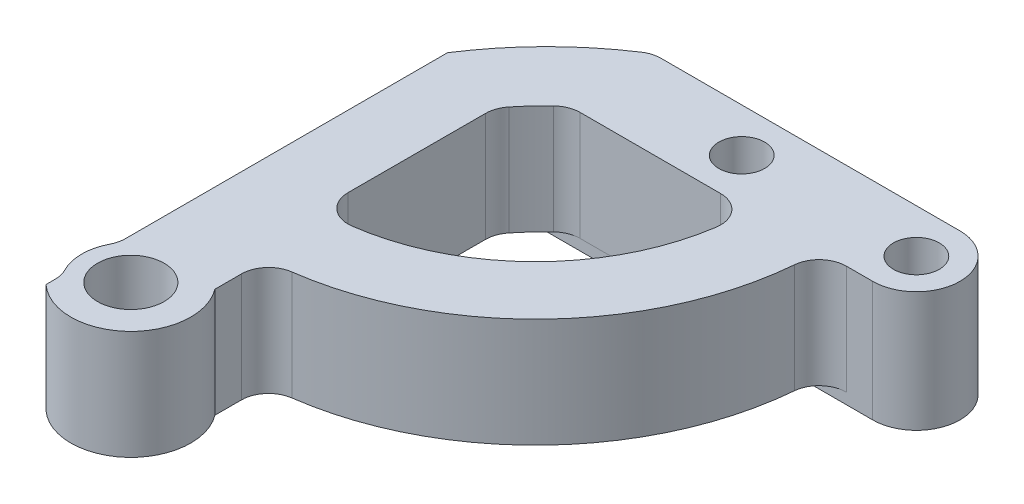
SolidWorks part; units mm, degrees
ref_plane "Front" through (0, 0, 0) normal (0, 0, 1) x (1, 0, 0)
ref_plane "Top" through (0, 0, 0) normal (0, 1, 0) x (1, 0, 0)
ref_plane "Right" through (0, 0, 0) normal (1, 0, 0) x (0, 0, -1)
sketch "Sketch1" plane through (0, 0, 0) normal (0, 1, 0) x (1, 0, 0)
  line L1 (-115.2537, -11) -> (-131.7843, -11)
  line L2 (-141.618, -49.1231) -> (-141.618, -47.6052)
  line L3 (-135.0594, -14.5432) -> (-135.0767, -30.6507)
  line L6 (-133.5072, -41.7607) -> (-133.5072, -37.0672)
  line L7 (-141.618, -42.5351) -> (-141.618, -12.3375)
  line L8 (-104, -3) -> (-132.1358, -3)
  line L9 (-104, -11) -> (-108.8005, -11)
  circle A26 centre (-104, -7) radius 2.1
  circle A27 centre (-120, -7) radius 2.1
  arc A32 (-104, -11) -> (-104, -3) centre (-104, -7) ccw
  arc A38 (-133.5072, -37.0672) -> (-108.8005, -11) centre (-134.9051, -11) ccw
  arc A40 (-132.1358, -3) -> (-141.618, -12.3375) centre (-115.9362, -28.9341) ccw
  arc A44 (-131.7843, -11) -> (-135.0594, -14.5432) centre (-115.9362, -28.9341) ccw
  arc A45 (-135.0767, -30.6507) -> (-115.2537, -11) centre (-134.9051, -11) ccw
  circle A50 centre (-137.9001, -45.0701) radius 3.05
  arc A52 (-141.618, -49.1231) -> (-133.5072, -41.7607) centre (-137.9001, -45.0701) ccw
  arc A53 (-141.618, -42.5351) -> (-141.618, -47.6052) centre (-137.9001, -45.0701) ccw
extrude "Boss-Extrude1" add sketch "Sketch1" along normal blind 11
fillet "Fillet1" radius 2.5 9 edges at (-132.1358, 5.5, 3) (-108.8005, 5.5, 11) (-135.0594, 5.5, 14.5432) (-135.0767, 5.5, 30.6507) (-115.2537, 5.5, 11) (-131.7843, 5.5, 11) (-133.5072, 5.5, 37.0672) (-141.618, 5.5, 42.5351) (-141.618, 5.5, 47.6052)
sketch "Sketch3" plane through (0, 0, 0) normal (0, -1, 0) x (1, 0, 0)
  line L0 (-104, 11) -> (-106.4099, 11) construction
  line L1 (-151.5816, 64.1144) -> (-89.5305, 64.1144)
  line L2 (-151.5816, 64.1144) -> (-151.5816, 11)
  line L3 (-151.5816, 11) -> (-89.5305, 11)
  line L4 (-89.5305, 64.1144) -> (-89.5305, 11)
  dimension "D1" = 0
extrude "Cut-Extrude2" cut sketch "Sketch3" against normal blind 1
